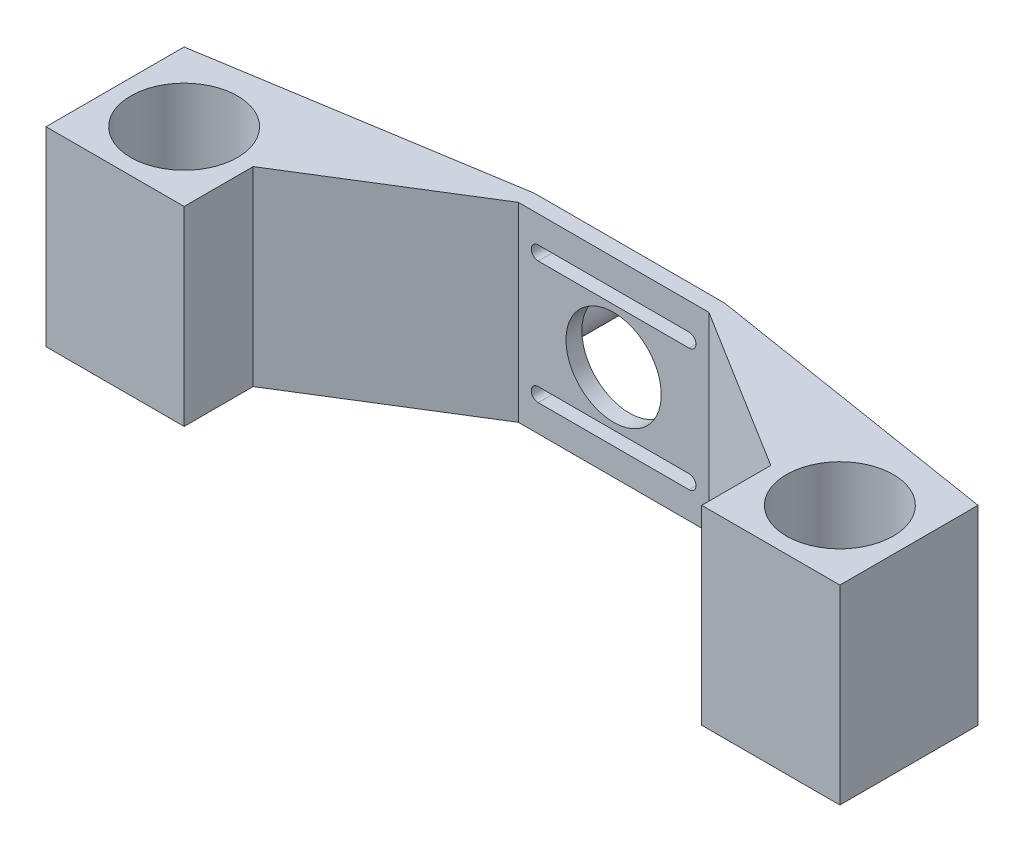
SolidWorks part; units mm, degrees
ref_plane "Front Plane" through (0, 0, 0) normal (0, 0, 1) x (1, 0, 0)
ref_plane "Top Plane" through (0, 0, 0) normal (0, 1, 0) x (1, 0, 0)
ref_plane "Right Plane" through (0, 0, 0) normal (1, 0, 0) x (0, 0, -1)
sketch "Sketch2" plane through (0, 0, 0) normal (0, 1, 0) x (1, 0, 0)
  line L0 (-17.4, -17.4) -> (82.6, -17.4) construction
  line L1 (-17.4, -17.4) -> (17.4, -17.4)
  line L2 (-17.4, -17.4) -> (-17.4, 17.4)
  line L5 (0, 17.4) -> (0, -17.4) construction
  line L6 (-17.4, 0) -> (17.4, 0) construction
  line L7 (82.6, -17.4) -> (82.6, 29.6) construction
  line L8 (17.4, -17.4) -> (17.4, 0)
  line L9 (82.6, 29.6) -> (58.6, 29.6)
  line L10 (82.6, 29.6) -> (82.6, 25.6)
  line L11 (82.6, 25.6) -> (58.6, 25.6)
  line L13 (17.4, 0) -> (58.6, 25.6)
  line L14 (58.6, 29.6) -> (-17.4, 17.4)
  circle A0 centre (0, 0) radius 13.45
  point P0 (0, 0)
  dimension "D3" = 26.9
  dimension "D8" = 17.4
  dimension "D9" = 17.4
  dimension "D1" = 34.8
  dimension "D2" = 34.8
  dimension "D4" = 100
  dimension "D5" = 47
  dimension "D6" = 24
  dimension "D7" = 4
extrude "Boss-Extrude1" add sketch "Sketch2" along normal blind 48
sketch3d "3DSketch1"
  line L0 (82.6, 0, -29.6) -> (82.6, 0, -25.6) construction
  line L1 (82.6, 0, -25.6) -> (82.6, 48, -25.6) construction
ref_plane "Plane1" through (82.6, 0, 0) normal (1, 0, 0) x (0, 0, -1)
mirror "Mirror1" about plane through (82.6, 0, 0) normal (1, 0, 0) of "Boss-Extrude1"
sketch "Sketch4" plane through (0, 0, -29.6) normal (0, 0, -1) x (-1, 0, 0)
  line L0 (-106.6, 24) -> (-58.6, 24) construction
  line L1 (-58.6, 48) -> (-58.6, 0) construction
  line L2 (-101.6, 8.55) -> (-63.6, 8.55) construction
  line L3 (-101.6, 10.3) -> (-63.6, 10.3)
  line L4 (-82.6, 0) -> (-82.6, 48) construction
  line L5 (-101.6, 6.8) -> (-63.6, 6.8)
  line L6 (-101.6, 39.45) -> (-63.6, 39.45) construction
  line L7 (-101.6, 37.7) -> (-63.6, 37.7)
  line L8 (-101.6, 41.2) -> (-63.6, 41.2)
  arc A0 (-101.6, 10.3) -> (-101.6, 6.8) centre (-101.6, 8.55) ccw
  arc A1 (-63.6, 6.8) -> (-63.6, 10.3) centre (-63.6, 8.55) ccw
  arc A2 (-101.6, 37.7) -> (-101.6, 41.2) centre (-101.6, 39.45) cw
  arc A3 (-63.6, 41.2) -> (-63.6, 37.7) centre (-63.6, 39.45) cw
  circle A4 centre (-82.6, 24) radius 12
  point P5 (-82.6, 24)
  point P7 (-82.6, 8.55)
  point P17 (-82.6, 39.45)
  dimension "D4" = 24
  dimension "D1" = 15.45
  dimension "D2" = 1.75
  dimension "D3" = 38
extrude "Cut-Extrude1" cut sketch "Sketch4" against normal blind 48
ref_plane "Plane2" through (0, 0, -29.6) normal (0, 0, -1) x (-1, 0, 0)
sketch "Sketch5" plane through (0, 0, -29.6) normal (0, 0, -1) x (-1, 0, 0)
  line L0 (-82.6, 24) -> (8.0606, 24) construction
  line L1 (-82.6, 0) -> (-82.6, 48) construction
  circle A2 centre (-62.1, 24) radius 4
  circle A3 centre (-62.1, 24) radius 7
  dimension "D1" = 8
  dimension "D3" = 3
  dimension "D2" = 20.5
extrude "Boss-Extrude2" add sketch "Sketch5" against normal blind 2
sketch "Sketch6" plane through (0, 0, -29.6) normal (0, 0, -1) x (-1, 0, 0)
  line L0 (-82.6, 24) -> (8.0606, 24) construction
  circle A2 centre (-62.1, 24) radius 4
  circle A3 centre (-62.1, 24) radius 7
  dimension "D1" = 8
  dimension "D3" = 3
  dimension "D2" = 20.5
extrude "Boss-Extrude3" add sketch "Sketch6" along normal blind 13
